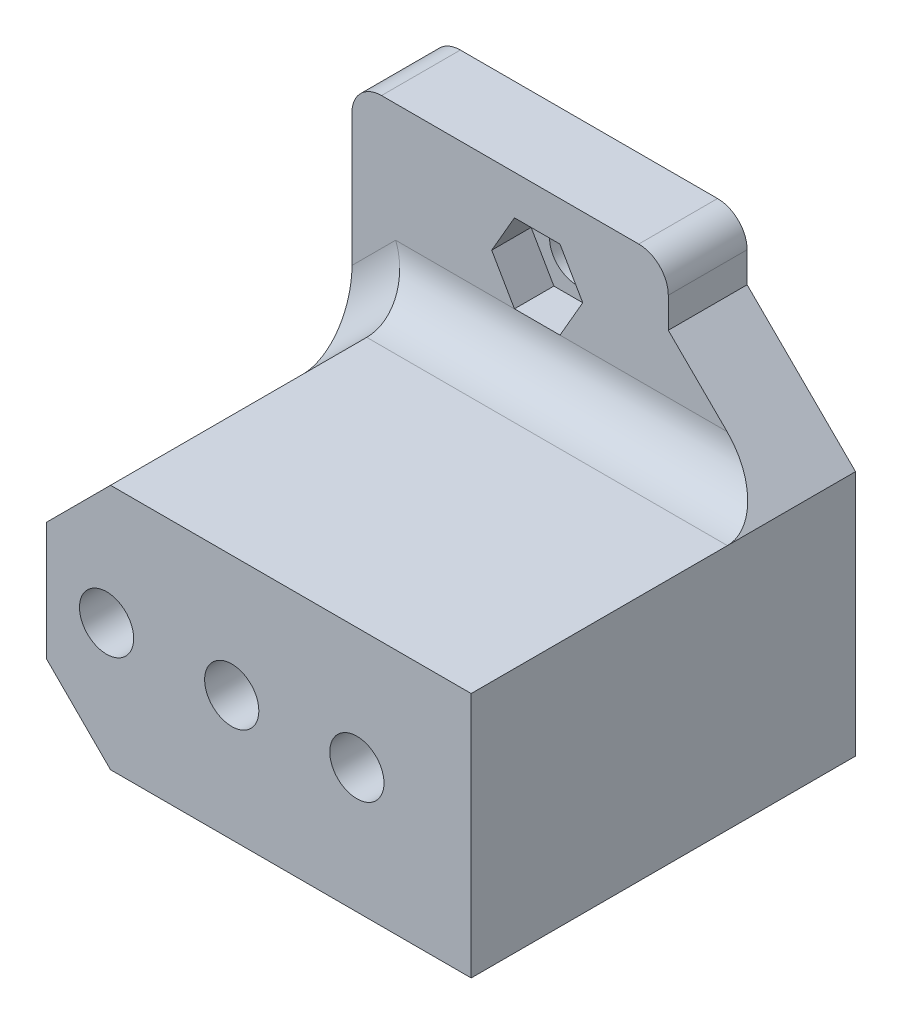
SolidWorks part; units mm, degrees
ref_plane "Front Plane" through (0, 0, 0) normal (0, 0, 1) x (1, 0, 0)
ref_plane "Top Plane" through (0, 0, 0) normal (0, 1, 0) x (1, 0, 0)
ref_plane "Right Plane" through (0, 0, 0) normal (1, 0, 0) x (0, 0, -1)
sketch "Sketch1" plane through (0, 0, 0) normal (0, 0, 1) x (1, 0, 0)
  line L0 (0, 0) -> (-43.1, 0)
  line L1 (-43.1, 0) -> (-43.1, 42)
  line L2 (-43.1, 42) -> (-11, 42)
  line L4 (0, 25) -> (0, 0)
  line L5 (-11, 42) -> (-11, 35.9202)
  line L6 (-11, 35.9202) -> (0, 25)
  circle A0 centre (-11.6, 12.7) radius 2.75
  circle A1 centre (-24.3, 12.7) radius 2.75
  circle A2 centre (-37, 12.7) radius 2.75
  circle A3 centre (-24.3, 34) radius 2.75
  dimension "D6" = 5.5
  dimension "D7" = 11.6
  dimension "D8" = 12.7
  dimension "D9" = 12.7
  dimension "D10" = 12.7
  dimension "D11" = 34
  dimension "D1" = 25
  dimension "D2" = 15.5
  dimension "D3" = 43.1
  dimension "D4" = 42
  dimension "D5" = 11
extrude "Boss-Extrude1" add sketch "Sketch1" along normal blind 8
sketch "Sketch2" plane through (0, 0, 8) normal (0, 0, 1) x (1, 0, 0)
  line L0 (0, 25) -> (-43.1, 25)
  line L6 (0, 0) -> (0, 25)
  line L7 (0, 25) -> (-11, 35.9202)
  line L8 (-11, 35.9202) -> (-11, 42)
  line L9 (-11, 42) -> (-43.1, 42)
  line L10 (-43.1, 42) -> (-43.1, 0)
  line L11 (-43.1, 0) -> (0, 0)
  line L12 (0, 0) -> (0, 25)
  line L16 (-43.1, 25) -> (-43.1, 0)
  line L17 (-43.1, 0) -> (0, 0)
  circle A0 centre (-11.6, 12.7) radius 2.75 construction
  circle A1 centre (-24.3, 12.7) radius 2.75 construction
  circle A2 centre (-37, 12.7) radius 2.75 construction
  circle A3 centre (-11.6, 12.7) radius 2.75
  circle A4 centre (-24.3, 12.7) radius 2.75
  circle A5 centre (-37, 12.7) radius 2.75
  dimension "D1" = 0
extrude "Boss-Extrude2" add sketch "Sketch2" along normal blind 31
chamfer "Chamfer1" distance 6.5 angle 45 2 edges at (-43.1, 25, 23.5) (-43.1, 0, 19.5)
fillet "Fillet1" radius 5 2 edges at (-39.85, 21.75, 8) (-18.3, 25, 8)
sketch "Sketch3" plane through (0, 0, 8) normal (0, 0, 1) x (1, 0, 0)
  line L1 (-19.6812, 34) -> (-21.9906, 38)
  line L2 (-21.9906, 38) -> (-26.6094, 38)
  line L3 (-26.6094, 38) -> (-28.9188, 34)
  line L4 (-28.9188, 34) -> (-26.6094, 30)
  line L5 (-26.6094, 30) -> (-21.9906, 30)
  line L6 (-21.9906, 30) -> (-19.6812, 34)
  circle A0 centre (-24.3, 34) radius 4 construction
  dimension "D1" = 8
extrude "Cut-Extrude1" cut sketch "Sketch3" against normal blind 4
fillet "Fillet2" radius 3 2 edges at (-11, 42, 4) (-43.1, 42, 4)
ref_plane "Plane1" through (20, 0, 0) normal (1, 0, 0) x (0, 0, -1)
